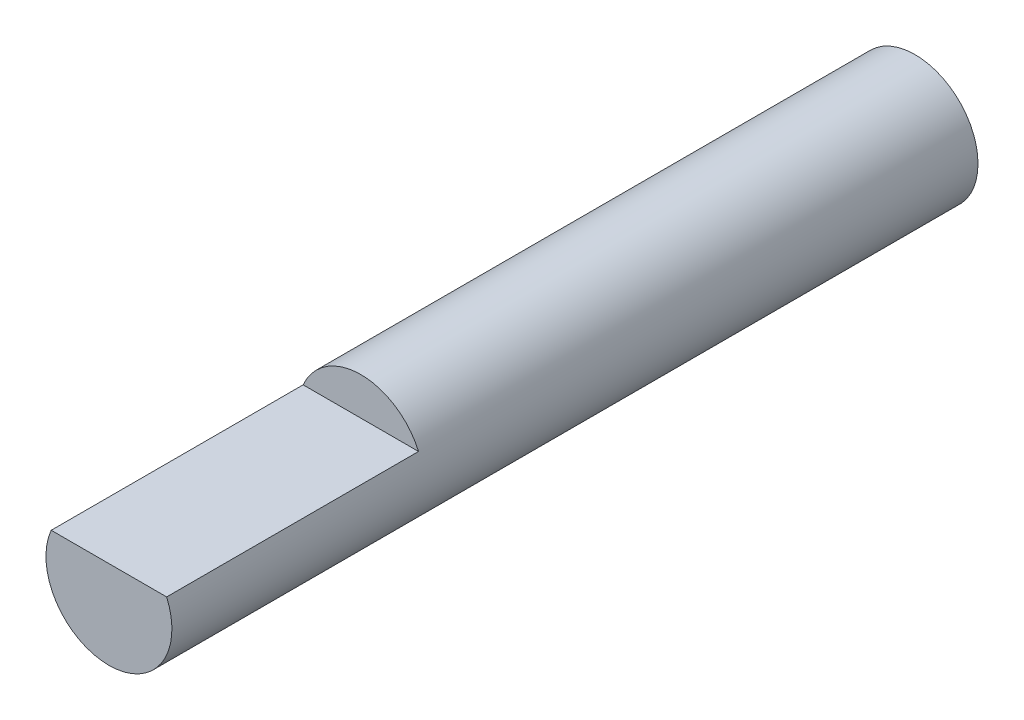
SolidWorks part; units mm, degrees
ref_plane "Alzado" through (0, 0, 0) normal (0, 0, 1) x (1, 0, 0)
ref_plane "Planta" through (0, 0, 0) normal (0, 1, 0) x (1, 0, 0)
ref_plane "Vista lateral" through (0, 0, 0) normal (1, 0, 0) x (0, 0, -1)
sketch "Croquis2" plane through (0, 0, 0) normal (0, 0, 1) x (1, 0, 0)
  circle A0 centre (0, 0) radius 2.5
  dimension "D1" = 5
extrude "Saliente-Extruir1" add sketch "Croquis2" along normal blind 32 contours A0
sketch "Croquis3" plane through (0, 0, 32) normal (0, 0, 1) x (1, 0, 0)
  line L0 (0, 0) -> (0, 1) construction
  line L1 (-2.2913, 1) -> (2.2913, 1)
  circle A0 centre (0, 0) radius 2.5 construction
  arc A1 (2.2913, 1) -> (-2.2913, 1) centre (0, 0) ccw
extrude "Cortar-Extruir1" cut sketch "Croquis3" against normal blind 10
